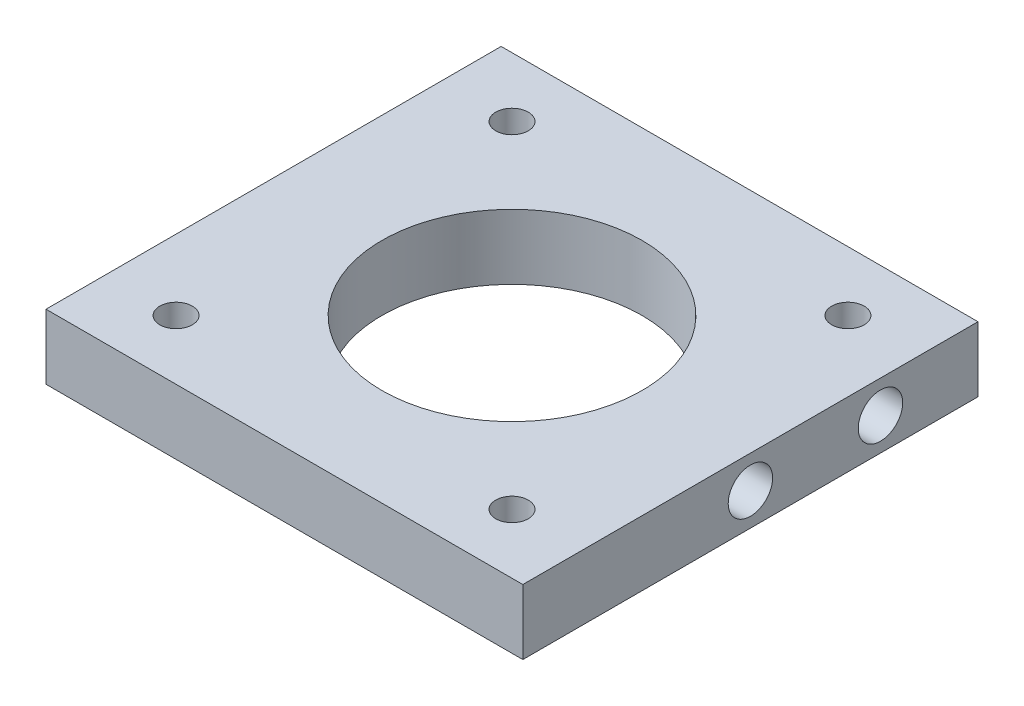
SolidWorks part; units mm, degrees
ref_plane "Front" through (0, 0, 0) normal (0, 0, 1) x (1, 0, 0)
ref_plane "Top" through (0, 0, 0) normal (0, 1, 0) x (1, 0, 0)
ref_plane "Right" through (0, 0, 0) normal (1, 0, 0) x (0, 0, -1)
sketch "Sketch1" plane through (0, 0, 0) normal (0, 0, 1) x (1, 0, 0)
  line L6 (-22, -3) -> (22, -3)
  line L9 (-22, -3) -> (-22, 3)
  line L10 (-22, 3) -> (22, 3)
  line L11 (22, -3) -> (22, 3)
  line L12 (-22, -3) -> (22, 3) construction
  line L13 (-22, 3) -> (22, -3) construction
  point P0 (0, 0)
  dimension "D1" = 6
  dimension "D2" = 44
extrude "Boss-Extrude1" add sketch "Sketch1" along normal blind 42
sketch "Sketch5" plane through (0, 3, 0) normal (0, 1, 0) x (1, 0, 0)
  line L0 (-22, -42) -> (22, 0) construction
  line L2 (-15.5, -5.5) -> (15.5, -5.5) construction
  line L3 (-15.5, -5.5) -> (-15.5, -36.5) construction
  line L4 (-15.5, -36.5) -> (15.5, -36.5) construction
  line L5 (15.5, -5.5) -> (15.5, -36.5) construction
  line L6 (-15.5, -5.5) -> (15.5, -36.5) construction
  line L7 (-15.5, -36.5) -> (15.5, -5.5) construction
  circle A0 centre (0, -21) radius 12
  circle A1 centre (-15.5, -5.5) radius 1.5
  circle A2 centre (15.5, -5.5) radius 1.5
  circle A3 centre (15.5, -36.5) radius 1.5
  circle A4 centre (-15.5, -36.5) radius 1.5
  dimension "D1" = 24
  dimension "D3" = 3
  dimension "D4" = 3
  dimension "D5" = 3
  dimension "D6" = 3
  dimension "D2" = 31
extrude "Cut-Extrude4" cut sketch "Sketch5" against normal up to next
sketch "Sketch6" plane through (-22, 0, 0) normal (-1, 0, 0) x (0, 0, 1)
  line L0 (21, 3) -> (21, -3) construction
  line L1 (42, 3) -> (0, 3) construction
  line L2 (42, -3) -> (0, -3) construction
  circle A0 centre (9, 0) radius 2.05
  circle A1 centre (21, 0) radius 2.05
  point P10 (21, 0)
  dimension "D1" = 4.1
  dimension "D2" = 4.1
  dimension "D3" = 12
extrude "Cut-Extrude5" cut sketch "Sketch6" against normal blind 6
sketch "Sketch7" plane through (22, 0, 0) normal (1, 0, 0) x (0, 0, -1)
  circle A0 centre (-9, 0) radius 2.05 construction
  circle A1 centre (-21, 0) radius 2.05 construction
  circle A2 centre (-9, 0) radius 2.05
  circle A3 centre (-21, 0) radius 2.05
extrude "Cut-Extrude6" cut sketch "Sketch7" against normal blind 6
